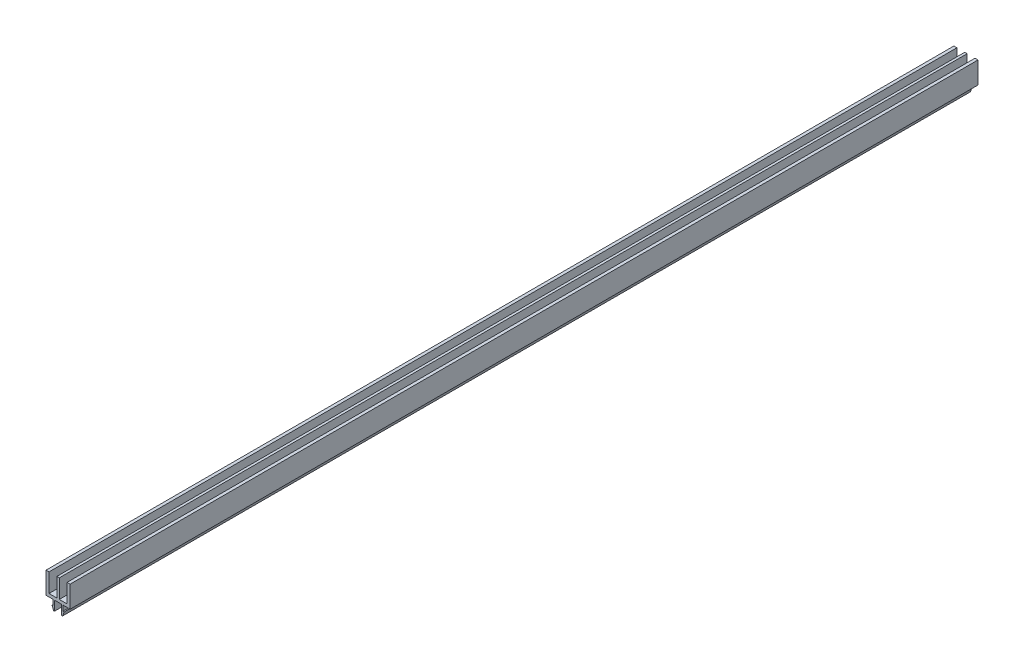
SolidWorks part; units mm, degrees
ref_plane "Plan de face" through (0, 0, 0) normal (0, 0, 1) x (1, 0, 0)
ref_plane "Plan de dessus" through (0, 0, 0) normal (0, 1, 0) x (1, 0, 0)
ref_plane "Plan de droite" through (0, 0, 0) normal (1, 0, 0) x (0, 0, -1)
ref_plane "Plan1" through (0, 0, 50) normal (0, 0, 1) x (1, 0, 0)
sketch "Esquisse1" plane through (0, 0, 50) normal (0, 0, 1) x (1, 0, 0)
  line L0 (-1, 2.5) -> (-7.5, 2.5)
  line L1 (-7.5, 2.5) -> (-7.5, 18)
  line L2 (-7.5, 18) -> (-10, 18)
  line L3 (-10, 18) -> (-10, 0)
  line L4 (-10, 0) -> (-4, 0)
  line L5 (-4, 0) -> (-4, -4.5)
  line L6 (-4, -4.5) -> (-5, -4.5)
  line L7 (-5, -4.5) -> (-3.75, -8)
  line L8 (-3.75, -8) -> (-3, -8)
  line L9 (-3, -8) -> (-3, 0)
  line L10 (-3, 0) -> (3, 0)
  line L11 (3, 0) -> (3, -8)
  line L12 (3, -8) -> (3.75, -8)
  line L13 (3.75, -8) -> (5, -4.5)
  line L14 (5, -4.5) -> (4, -4.5)
  line L15 (4, -4.5) -> (4, 0)
  line L16 (4, 0) -> (10, 0)
  line L17 (10, 0) -> (10, 18)
  line L18 (10, 18) -> (7.5, 18)
  line L19 (7.5, 18) -> (7.5, 2.5)
  line L20 (7.5, 2.5) -> (1, 2.5)
  line L21 (1, 2.5) -> (1, 18)
  line L22 (1, 18) -> (-1, 18)
  line L23 (-1, 18) -> (-1, 2.5)
extrude "Boss.-Extru.1" add sketch "Esquisse1" against normal blind 752
